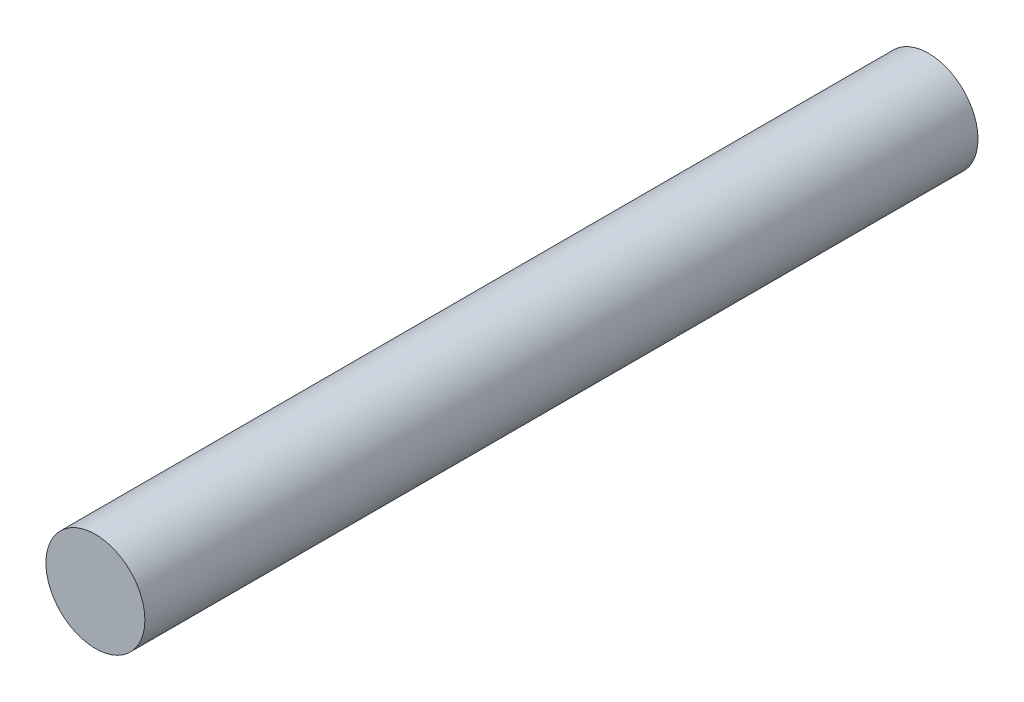
SolidWorks part; units mm, degrees
ref_plane "Alzado" through (0, 0, 0) normal (0, 0, 1) x (1, 0, 0)
ref_plane "Planta" through (0, 0, 0) normal (0, 1, 0) x (1, 0, 0)
ref_plane "Vista lateral" through (0, 0, 0) normal (1, 0, 0) x (0, 0, -1)
sketch "Croquis1" plane through (0, 0, 0) normal (0, 0, 1) x (1, 0, 0)
  circle A0 centre (0, 0) radius 2.575
  dimension "D1" = 5.15
extrude "Saliente-Extruir1" add sketch "Croquis1" along normal blind 43.35
